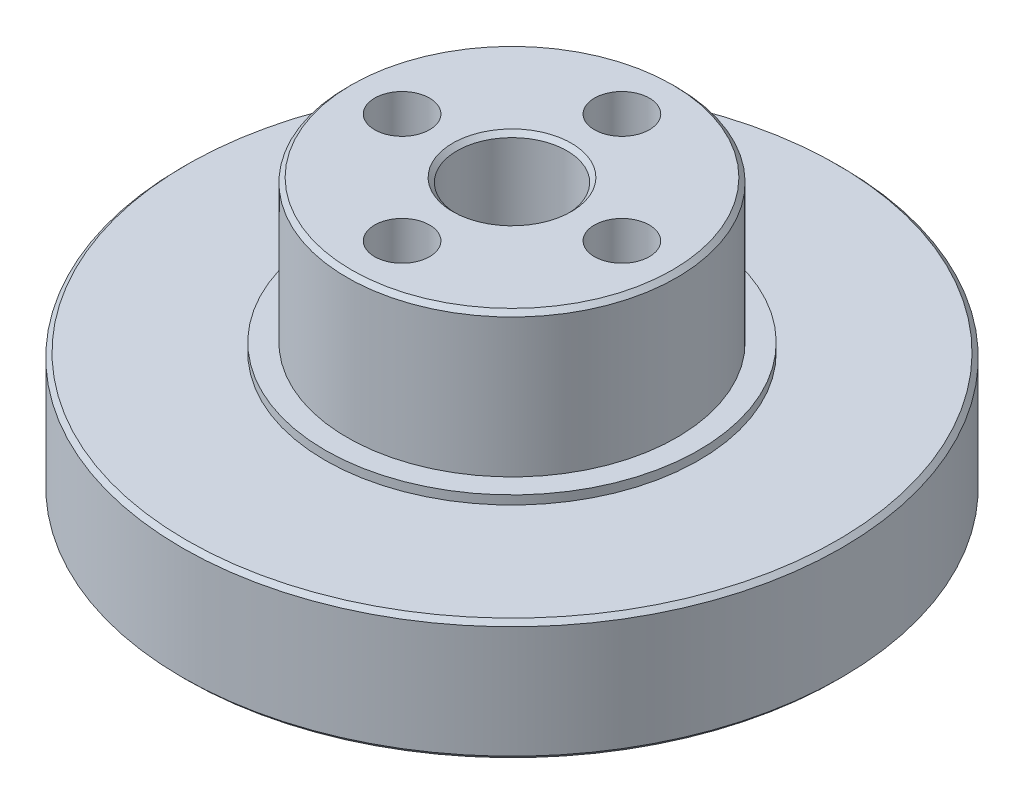
SolidWorks part; units mm, degrees
ref_plane "前视基准面" through (0, 0, 0) normal (0, 0, 1) x (1, 0, 0)
ref_plane "上视基准面" through (0, 0, 0) normal (0, 1, 0) x (1, 0, 0)
ref_plane "右视基准面" through (0, 0, 0) normal (1, 0, 0) x (0, 0, -1)
other "Configuration Table"
sketch "草图1" plane through (0, 0, 0) normal (0, 1, 0) x (1, 0, 0)
  circle A0 centre (0, 0) radius 11.525 construction
  circle A1 centre (0, 11.525) radius 2.075
  circle A2 centre (9.9809, 5.7625) radius 2.075
  circle A3 centre (9.9809, -5.7625) radius 2.075
  circle A4 centre (0, -11.525) radius 2.075
  circle A5 centre (-9.9809, -5.7625) radius 2.075
  circle A6 centre (-9.9809, 5.7625) radius 2.075
  circle A8 centre (0, 0) radius 15
  point P18 (0, 0)
  dimension "D1" = 23.05
  dimension "D2" = 4.15
  dimension "D5" = 30
  dimension "D3" = 6
extrude "凸台-拉伸1" add sketch "草图1" along normal blind 4
sketch "草图2" plane through (0, 4, 0) normal (0, 1, 0) x (1, 0, 0)
  circle A0 centre (0, 0) radius 15
extrude "凸台-拉伸2" add sketch "草图2" along normal blind 1.5
sketch "草图3" plane through (0, 5.5, 0) normal (0, 1, 0) x (1, 0, 0)
  circle A0 centre (0, 0) radius 8.5
  dimension "D1" = 17
extrude "凸台-拉伸3" add sketch "草图3" along normal blind 0.4
sketch "草图4" plane through (0, 5.9, 0) normal (0, 1, 0) x (1, 0, 0)
  circle A0 centre (0, 0) radius 7.5
  dimension "D1" = 15
extrude "凸台-拉伸4" add sketch "草图4" along normal blind 6.5
sketch "草图5" plane through (0, 12.4, 0) normal (0, 1, 0) x (1, 0, 0)
  circle A0 centre (0, 5) radius 1.25
  circle A1 centre (5, 0) radius 1.25
  circle A2 centre (0, -5) radius 1.25
  circle A3 centre (-5, 0) radius 1.25
  circle A4 centre (0, 0) radius 2.5
  point P12 (0, 0)
  dimension "D1" = 2.5
  dimension "D2" = 5
  dimension "D4" = 5
  dimension "D3" = 4
extrude "切除-拉伸1" cut sketch "草图5" against normal blind 5
chamfer "倒角1" distance 0.2 angle 45 10 edges at (-9.9809, 0, -3.6875) (-9.9809, 0, 7.8375) (0, 0, 13.6) (9.9809, 0, 7.8375) (9.9809, 0, -3.6875) (0, 0, -9.45) (0, 0, 15) (0, 12.4, 7.5) (0, 5.5, 15) (0, 12.4, 2.5)
sketch "草图7" plane through (0, 7.4, 0) normal (0, 1, 0) x (1, 0, 0)
  circle A2 centre (0, 0) radius 2.5 construction
  circle A3 centre (0, 0) radius 2.5
extrude "切除-拉伸4" cut sketch "草图7" against normal through all
sketch "草图8" plane through (0, 0, 0) normal (0, -1, 0) x (-1, 0, 0)
  circle A0 centre (0, 0) radius 6
  dimension "D1" = 6
extrude "切除-拉伸5" cut sketch "草图8" against normal blind 2
chamfer "倒角2" distance 0.5 angle 45 3 edges at (0, 0, -6) (0, 2, -2.5) (0, 2, -6)
